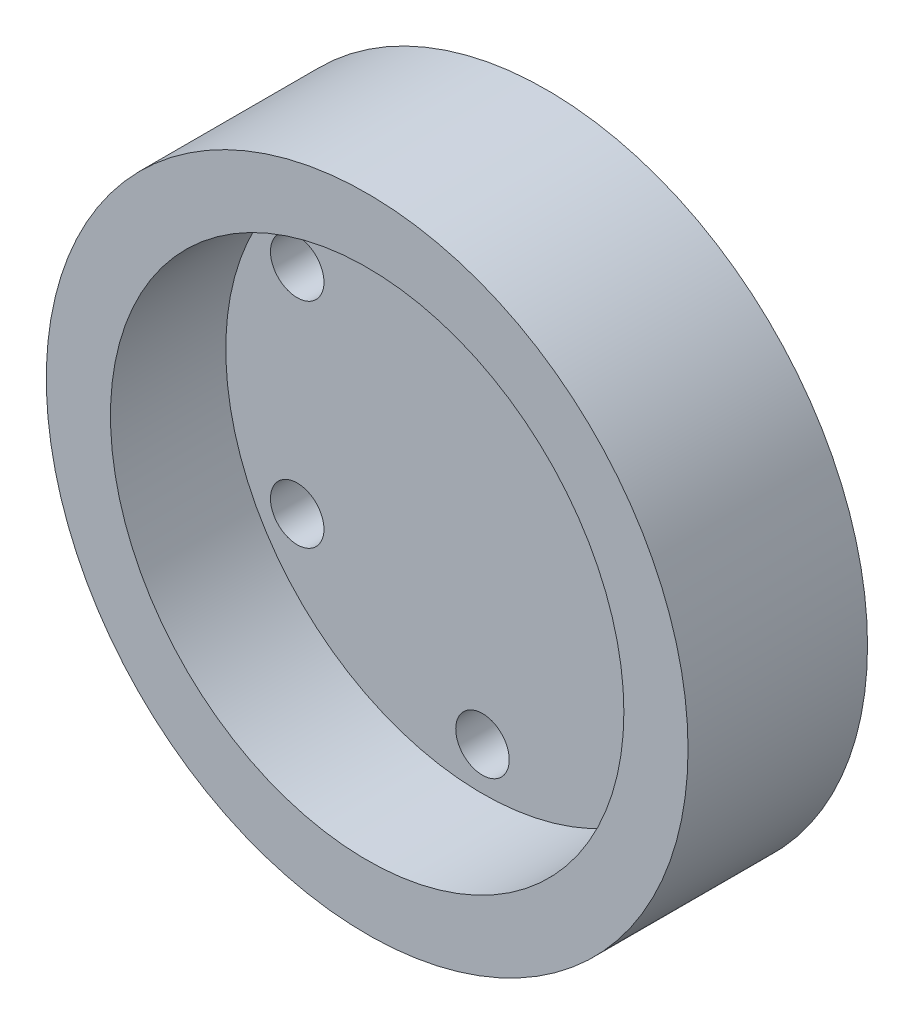
SolidWorks part; units mm, degrees
ref_plane "Front Plane" through (0, 0, 0) normal (0, 0, 1) x (1, 0, 0)
ref_plane "Top Plane" through (0, 0, 0) normal (0, 1, 0) x (1, 0, 0)
ref_plane "Right Plane" through (0, 0, 0) normal (1, 0, 0) x (0, 0, -1)
sketch "Sketch2" plane through (0, 0, 0) normal (0, 0, 1) x (1, 0, 0)
  circle A0 centre (0, 0) radius 15
  dimension "D1" = 30
extrude "Boss-Extrude1" add sketch "Sketch2" along normal blind 8.39
shell "Shell1" thickness 3
sketch "Sketch3" plane through (0, 0, 0) normal (0, 0, -1) x (-1, 0, 0)
  circle A0 centre (0, 10) radius 1.25
  circle A1 centre (0, 0) radius 15 construction
  circle A2 centre (8.6603, 5) radius 1.25
  circle A3 centre (8.6603, -5) radius 1.25
  circle A4 centre (0, -10) radius 1.25
  circle A5 centre (-8.6603, -5) radius 1.25
  circle A6 centre (-8.6603, 5) radius 1.25
  point P16 (0, 0)
  dimension "D1" = 2.5
  dimension "D2" = 10
  dimension "D3" = 6
extrude "Cut-Extrude1" cut sketch "Sketch3" against normal blind 5
scale "Scale1" scale about centroid uniform scaling yes scale factor 0.5
